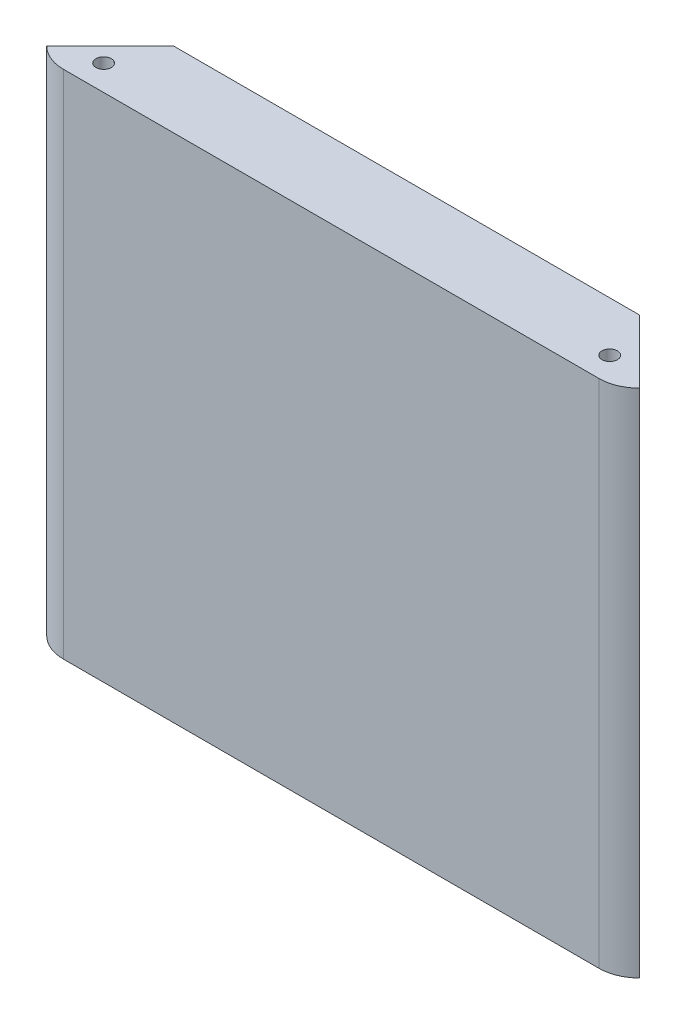
SolidWorks part; units mm, degrees
material "ПК/АБС"
ref_plane "Спереди" through (0, 0, 0) normal (0, 0, 1) x (1, 0, 0)
ref_plane "Сверху" through (0, 0, 0) normal (0, 1, 0) x (1, 0, 0)
ref_plane "Справа" through (0, 0, 0) normal (1, 0, 0) x (0, 0, -1)
sketch "Эскиз1" plane through (0, 0, 0) normal (0, 0, 1) x (1, 0, 0)
  line L1 (-40.95, 33.95) -> (40.95, 33.95)
  line L2 (-40.95, 33.95) -> (-40.95, -33.95)
  line L3 (-40.95, -33.95) -> (40.95, -33.95)
  line L4 (40.95, 33.95) -> (40.95, -33.95)
  point P0 (0, 0)
extrude "Бобышка-Вытянуть1" add sketch "Эскиз1" against normal blind 10
sketch "Эскиз2" plane through (0, 0, -10) normal (0, 0, -1) x (-1, 0, 0)
  line L1 (-30.25, 30.25) -> (30.25, 30.25)
  line L2 (-30.25, 30.25) -> (-30.25, -30.25)
  line L3 (-30.25, -30.25) -> (30.25, -30.25)
  line L4 (30.25, 30.25) -> (30.25, -30.25)
  line L5 (-30.25, 30.25) -> (30.25, -30.25) construction
  line L6 (-30.25, -30.25) -> (30.25, 30.25) construction
  point P0 (0, 0)
extrude "Вырез-Вытянуть1" cut sketch "Эскиз2" against normal blind 8.5
sketch "Эскиз3" plane through (0, 33.95, 0) normal (0, 1, 0) x (1, 0, 0)
  line L0 (30.95, 10) -> (40.95, 0)
  line L1 (-30.95, 10) -> (-40.95, 10)
  line L2 (-40.95, 10) -> (-40.95, 0)
  line L3 (0, 10) -> (0, 17.5402)
  line L4 (-40.95, 10) -> (40.95, 10) construction
  line L5 (40.95, 10) -> (40.95, 0)
  line L6 (30.95, 10) -> (40.95, 10)
  line L9 (-30.95, 10) -> (-40.95, 0)
sketch "Эскиз4" plane through (0, -33.95, -40.95) normal (0, 1, 0) x (1, 0, 0)
  line L2 (39.383, -39.383) -> (40.95, -40.95)
  line L3 (40.95, -40.95) -> (35.6, -40.95)
  line L4 (-40.95, -40.95) -> (-35.6, -40.95)
  line L5 (-39.383, -39.383) -> (-40.95, -40.95)
  arc A0 (35.6, -40.95) -> (39.383, -39.383) centre (35.6, -35.6) ccw
  arc A1 (-35.6, -40.95) -> (-39.383, -39.383) centre (-35.6, -35.6) cw
  point P0 (-40.95, -40.95)
extrude "Вырез-Вытянуть4" cut sketch "Эскиз4" along normal up to next
sketch "Эскиз5" plane through (0, 33.95, 0) normal (0, 1, 0) x (1, 0, 0)
  point P2 (33.6321, 3.3821)
  point P5 (-33.6321, 3.3821)
hole_wizard "Отверстие обработанное метчиком M2.5x0.451" positions "Эскиз7" profile "Эскиз8" tap size "M2.5x0.45" standard "Ansi Metric"
sketch "Эскиз7" plane through (0, 33.95, 0) normal (0, 1, 0) x (1, 0, 0)
  point P0 (33.6321, 3.3821)
  point P4 (-33.6321, 3.3821)
sketch "Эскиз8" plane through (33.6321, 33.95, -3.3821) normal (1, 0, 0) x (0, 0, 1)
  line L0 (0, 0) -> (0, 5.6159)
  line L1 (0, 5.6159) -> (1.025, 5)
  line L2 (1.025, 5) -> (1.025, 0)
  line L5 (1.025, 0) -> (0, 0)
  line L10 (0, 5.6159) -> (-1.025, 5) construction
  line L11 (0, -6.35) -> (0, 107.95) construction
  dimension "Диаметр сверла" = 2.05
  dimension "Глубина сверла" = 5
  dimension "Угол заточки сверла" = 118
cosmetic thread "Отверстие резьбы1" parameters "D1"=5, "D2"=2.5
cosmetic thread "Отверстие резьбы2" parameters "D1"=5, "D2"=2.5
mirror "Зеркальное отражение1" about plane through (0, 0, 0) normal (0, 1, 0) of "Отверстие обработанное метчиком M2.5x0.451"
extrude "Вырез-Вытянуть5" cut sketch "Эскиз3" against normal up to next
